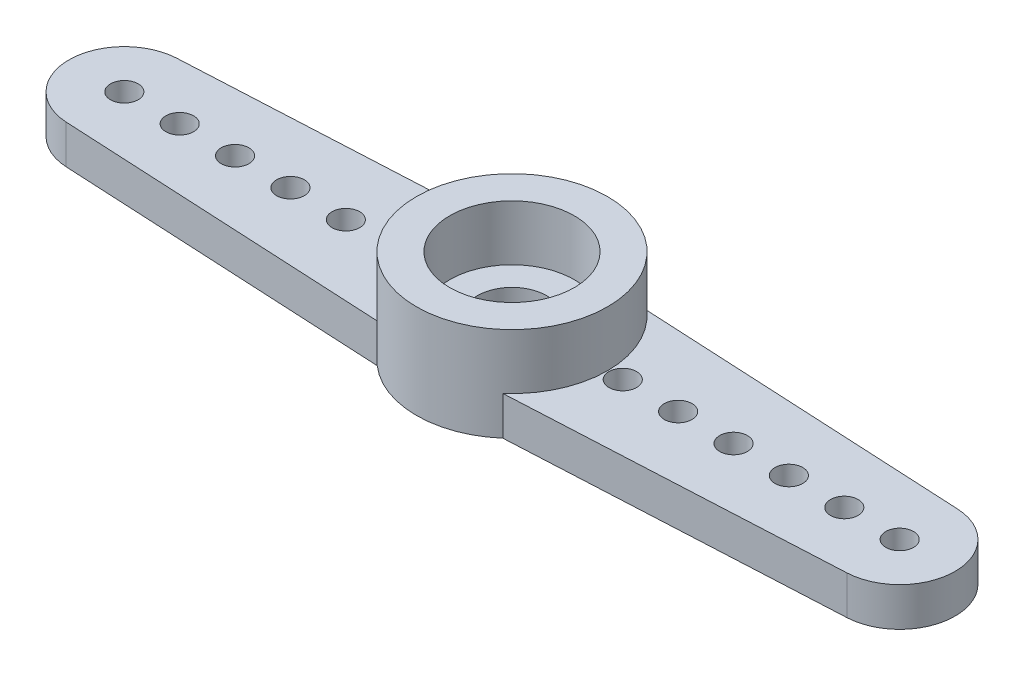
SolidWorks part; units mm, degrees
ref_plane "Plano frontal" through (0, 0, 0) normal (0, 0, 1) x (1, 0, 0)
ref_plane "Plano superior" through (0, 0, 0) normal (0, 1, 0) x (1, 0, 0)
ref_plane "Plano direito" through (0, 0, 0) normal (1, 0, 0) x (0, 0, -1)
sketch "Esboço1" plane through (0, 0, 0) normal (0, 1, 0) x (1, 0, 0)
  line L0 (-14, 0) -> (14, 0) construction
  line L1 (-14.1017, 1.9974) -> (-2.2677, 2.6)
  line L2 (2.2677, 2.6) -> (14.1017, 1.9974)
  line L3 (14.1017, -1.9974) -> (2.2677, -2.6)
  line L4 (-2.2677, -2.6) -> (-14.1017, -1.9974)
  line L5 (-2.2677, 2.6) -> (2.2677, 2.6) construction
  line L6 (2.2677, -2.6) -> (-2.2677, -2.6) construction
  arc A2 (-14.1017, 1.9974) -> (-14.1017, -1.9974) centre (-14, 0) ccw
  arc A3 (14.1017, 1.9974) -> (14.1017, -1.9974) centre (14, 0) cw
  arc A4 (-2.2677, 2.6) -> (2.2677, 2.6) centre (0, 0) cw
  arc A5 (-2.2677, -2.6) -> (2.2677, -2.6) centre (0, 0) ccw
  point P12 (0, 0)
  point P14 (0, 0)
  point P15 (0, 0)
  point P16 (0, 0)
  dimension "D1" = 3.45
  dimension "D4" = 2
  dimension "D2" = 5.2
  dimension "D3" = 28
extrude "Ressalto-extrusão1" add sketch "Esboço1" along normal blind 1.4
sketch "Esboço2" plane through (0, 1.4, 0) normal (0, 1, 0) x (1, 0, 0)
  circle A0 centre (0, 0) radius 3.45
extrude "Ressalto-extrusão2" add sketch "Esboço2" along normal blind 2
sketch "Esboço3" plane through (0, 3.4, 0) normal (0, 1, 0) x (1, 0, 0)
  circle A0 centre (0, 0) radius 2.25
  dimension "D1" = 4.5
extrude "Corte-extrusão1" cut sketch "Esboço3" against normal blind 2
sketch "Esboço4" plane through (0, 0, 0) normal (0, -1, 0) x (1, 0, 0)
  circle A0 centre (0, 0) radius 2.25
  dimension "D1" = 4.5
extrude "Corte-extrusão2" cut sketch "Esboço4" against normal blind 0.5
sketch "Esboço5" plane through (0, 0.5, 0) normal (0, -1, 0) x (1, 0, 0)
  circle A0 centre (0, 0) radius 1.25
  dimension "D1" = 2.5
extrude "Corte-extrusão3" cut sketch "Esboço5" against normal through all
sketch "Esboço6" plane through (0, 0, 0) normal (0, -1, 0) x (1, 0, 0)
  line L0 (-4, 0) -> (0, 0) construction
  line L1 (-4, 0) -> (-6, 0) construction
  circle A0 centre (-4, 0) radius 0.5
  circle A1 centre (-6, 0) radius 0.5
  circle A2 centre (-8, 0) radius 0.5
  circle A3 centre (-10, 0) radius 0.5
  circle A4 centre (-12, 0) radius 0.5
  circle A5 centre (-14, 0) radius 0.5
  dimension "D1" = 1
  dimension "D2" = 4
  dimension "D4" = 2
  dimension "D3" = 6
extrude "Corte-extrusão4" cut sketch "Esboço6" against normal through all
mirror "Espelhar1" about plane through (0, 0, 0) normal (1, 0, 0) of "Corte-extrusão4"
